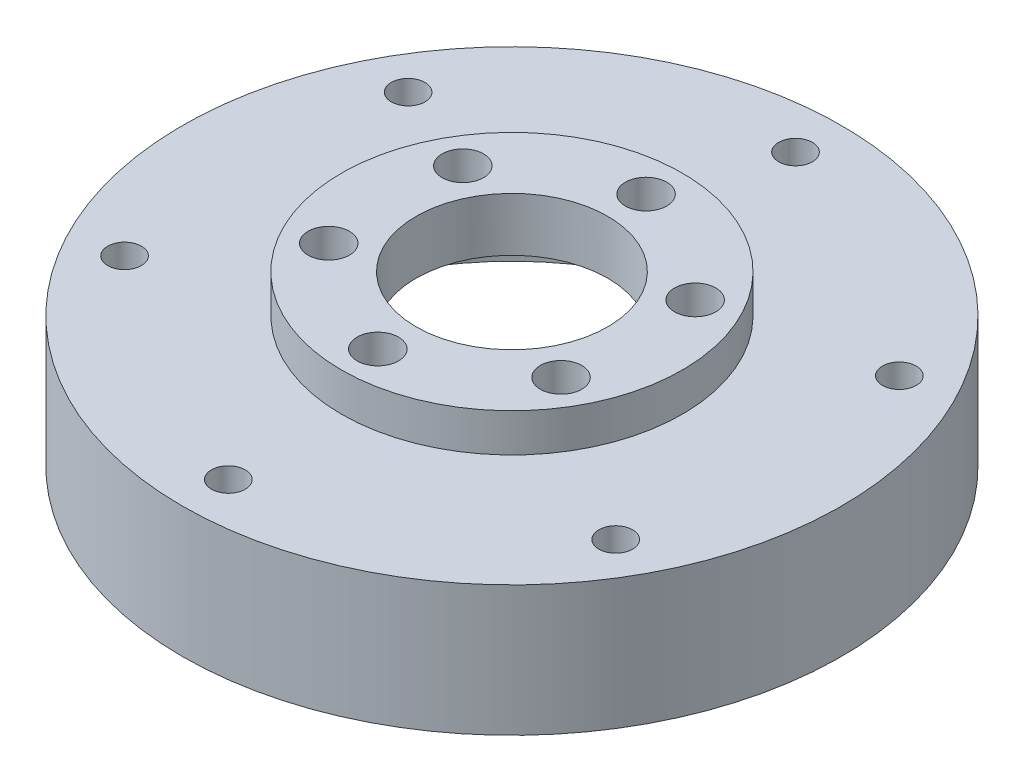
SolidWorks part; units mm, degrees
ref_plane "Front Plane" through (0, 0, 0) normal (0, 0, 1) x (1, 0, 0)
ref_plane "Top Plane" through (0, 0, 0) normal (0, 1, 0) x (1, 0, 0)
ref_plane "Right Plane" through (0, 0, 0) normal (1, 0, 0) x (0, 0, -1)
sketch "스케치22" plane through (0, 0, 0) normal (0, 1, 0) x (1, 0, 0)
  circle A0 centre (0, 0) radius 43
  circle A1 centre (0, 0) radius 22.5
  dimension "D1" = 86
  dimension "D2" = 45
extrude "보스-돌출5" add sketch "스케치22" along normal blind 17 contours A0
sketch "스케치24" plane through (0, 17, 0) normal (0, 1, 0) x (1, 0, 0)
  circle A0 centre (0, 0) radius 22.5 construction
  circle A2 centre (0, 0) radius 22.244
  dimension "D1" = 45
extrude "보스-돌출6" add sketch "스케치24" along normal blind 5
sketch "스케치25" plane through (0, 0, 0) normal (0, -1, 0) x (1, 0, 0)
  circle A3 centre (0, 0) radius 32.5 construction
  circle A4 centre (0, 0) radius 32.76
  dimension "D1" = 65
extrude "컷-돌출9" cut sketch "스케치25" against normal blind 15
sketch "스케치26" plane through (0, 22, 0) normal (0, 1, 0) x (1, 0, 0)
  circle A0 centre (0, 0) radius 12.5
  circle A1 centre (0, 0) radius 12.7
  dimension "D1" = 25
  dimension "D2" = 0.2
extrude "컷-돌출10" cut sketch "스케치26" against normal blind 10 contours A0
sketch "스케치27" plane through (0, 22, 0) normal (0, 1, 0) x (1, 0, 0)
  arc A0 (-2.692, 17.2917) -> (2.692, 17.2917) centre (0, 0) ccw
  circle A1 centre (0, 17.5) radius 2.7
  point P3 (0, 17.5)
  dimension "D1" = 35
  dimension "D2" = 5.4
sketch "스케치29" plane through (0, 17, 0) normal (0, 1, 0) x (1, 0, 0)
  line L0 (0, 0) -> (0, 48.7999) construction
  circle A0 centre (0, 0) radius 37
  circle A1 centre (0, 37) radius 2.2
  point P3 (0, 37)
  dimension "D1" = 74
  dimension "D2" = 4.4
extrude "컷-돌출11" cut sketch "스케치27" against normal blind 6.1 contours A1
pattern_circular "원형 패턴6" count 6 over 360 about axis through (0, 0, 0) along (0, 1, 0) of "컷-돌출11"
extrude "컷-돌출12" cut sketch "스케치29" against normal through all contours A1
pattern_circular "원형 패턴7" count 6 over 360 about axis through (0, 0, 0) along (0, 1, 0) of "컷-돌출12"
equation "\"Diameter\"= 86"
equation "\"D1@스케치22\"=\"Diameter\""
equation "\"Bearing_Diameter\"= 45"
equation "\"D1@스케치24\"=\"Bearing_Diameter\""
equation "\"Bearing_Height\"= 5"
equation "\"D1@보스-돌출6\"=\"Bearing_Height\""
equation "\"Inner_diameter\"= \"Motor_Diameter\" + 2"
equation "\"Center_Gap\"= 25"
equation "\"D1@스케치26\"=\"Center_Gap\""
equation "\"Shoulder_Pin_Line\"= 17.5 * 2"
equation "\"D1@스케치27\"=\"Shoulder_Pin_Line\""
equation "\"Screw_Placement_Diameter\"= 74"
equation "\"D1@스케치29\"=\"Screw_Placement_Diameter\""
equation "\"D2@스케치22\"=\"Bearing_Diameter\""
equation "\"Top_Shell_Height\"= 17"
equation "\"D1@보스-돌출5\"=\"Top_Shell_Height\""
equation "\"D1@컷-돌출9\"=\"Top_Shell_Height\"-2"
equation "\"TOL\"= 0.2mm"
equation "\"Shoulder_Pin_Diameter\"=4.4"
equation "\"M3-Thread-Hole\"= 4.4"
equation "\"D2@스케치29\"=\"M3-Thread-Hole\""
equation "\"Motor_Diameter\"= 63"
equation "\"D1@스케치25\"=\"Inner_diameter\""
equation "\"M4 - Thread - Hole\"= 5.9"
